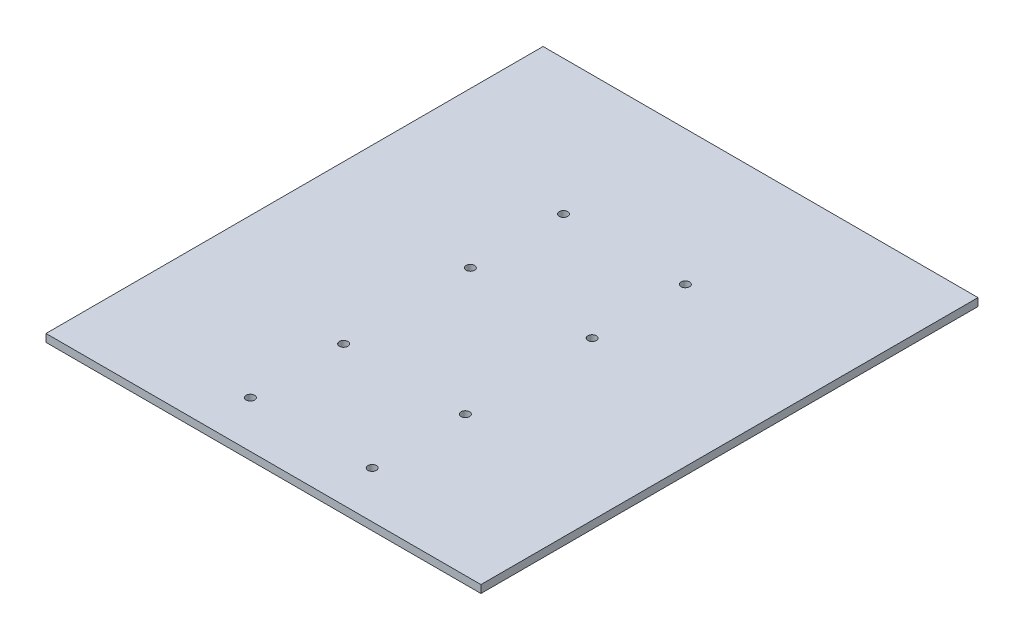
SolidWorks part; units mm, degrees
ref_plane "Front Plane" through (0, 0, 0) normal (0, 0, 1) x (1, 0, 0)
ref_plane "Top Plane" through (0, 0, 0) normal (0, 1, 0) x (1, 0, 0)
ref_plane "Right Plane" through (0, 0, 0) normal (1, 0, 0) x (0, 0, -1)
sketch "Sketch1" plane through (0, 0, 0) normal (0, 1, 0) x (1, 0, 0)
  line L1 (0, 0) -> (-177.8, 0)
  line L2 (0, 0) -> (0, -203.2)
  line L3 (0, -203.2) -> (-177.8, -203.2)
  line L4 (-177.8, 0) -> (-177.8, -203.2)
  dimension "D1" = 177.8
  dimension "D2" = 203.2
extrude "Boss-Extrude1" add sketch "Sketch1" along normal blind 3.175
hole_wizard "Tap Drill for #8-36 Tap1" positions "Sketch3" profile "Sketch2" hole size "#8-36" standard "ANSI Inch" end condition up to next
sketch "Sketch3" plane through (0, 3.175, 0) normal (0, 1, 0) x (1, 0, 0)
  point P0 (-114.3, -55.1271)
  point P3 (-64.5116, -55.1271)
  point P6 (-64.5116, -93.2271)
  point P9 (-114.3, -93.2271)
  point P12 (-113.2884, -146.05)
  point P15 (-113.2884, -184.15)
  point P18 (-63.5, -184.15)
  point P21 (-63.5, -146.05)
sketch "Sketch2" plane through (-114.3, 3.175, 55.1271) normal (1, 0, 0) x (0, 0, 1)
  line L0 (0, 0) -> (0, 3.175)
  line L1 (0, 3.175) -> (1.7272, 3.175)
  line L2 (1.7272, 3.175) -> (1.7272, 0)
  line L5 (1.7272, 0) -> (0, 0)
  line L11 (0, -6.35) -> (0, 107.95) construction
  dimension "Thru Hole Dia." = 3.4544
  dimension "Thru Hole Depth" = 3.175
